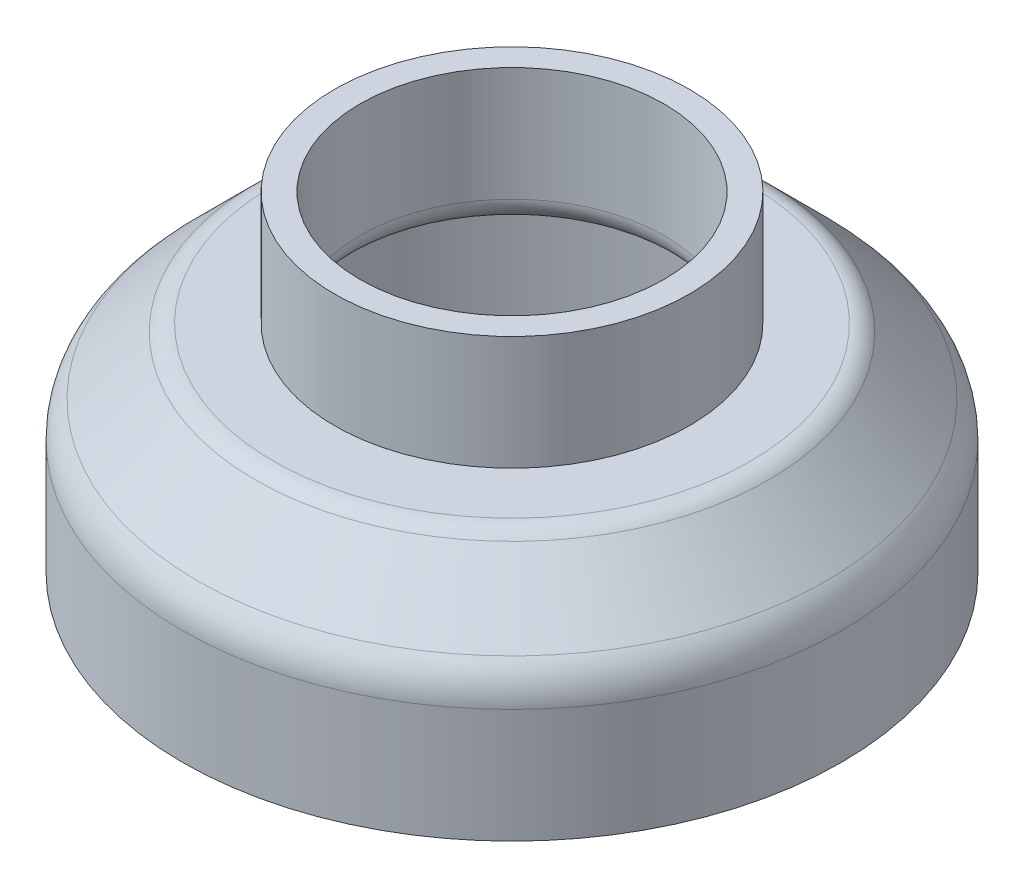
SolidWorks part; units mm, degrees
ref_plane "Plan de face" through (0, 0, 0) normal (0, 0, 1) x (1, 0, 0)
ref_plane "Plan de dessus" through (0, 0, 0) normal (0, 1, 0) x (1, 0, 0)
ref_plane "Plan de droite" through (0, 0, 0) normal (1, 0, 0) x (0, 0, -1)
sketch "Esquisse1" plane through (0, 0, 0) normal (0, 0, 1) x (1, 0, 0)
  line L0 (0, 0) -> (0, 65.6919) construction
  line L1 (7, 51.5839) -> (7, 47.0839)
  line L2 (7, 47.0839) -> (9.4142, 47.0839)
  line L3 (10.1213, 46.791) -> (12.4142, 44.4981)
  line L4 (13, 43.0839) -> (13, 38.5839)
  line L5 (12, 43.0839) -> (12, 38.5839)
  line L6 (9.4142, 46.0839) -> (11.7071, 43.791)
  line L7 (7, 46.0839) -> (9.4142, 46.0839)
  line L8 (6, 51.5839) -> (6, 47.0839)
  line L9 (6, 51.5839) -> (7, 51.5839)
  line L10 (12, 38.5839) -> (13, 38.5839)
  arc A0 (7, 46.0839) -> (6, 47.0839) centre (7, 47.0839) cw
  arc A1 (10.1213, 46.791) -> (9.4142, 47.0839) centre (9.4142, 46.0839) ccw
  arc A2 (12, 43.0839) -> (11.7071, 43.791) centre (11, 43.0839) ccw
  arc A3 (13, 43.0839) -> (12.4142, 44.4981) centre (11, 43.0839) ccw
  dimension "D2" = 1
  dimension "D3" = 2
  dimension "D4" = 45
  dimension "D5" = 4.5
  dimension "D6" = 4.5
  dimension "D7" = 6
  dimension "D8" = 13
  dimension "D9" = 13
  dimension "D1" = 1
revolve "Révolution1" add sketch "Esquisse1" angle 360 about L0
